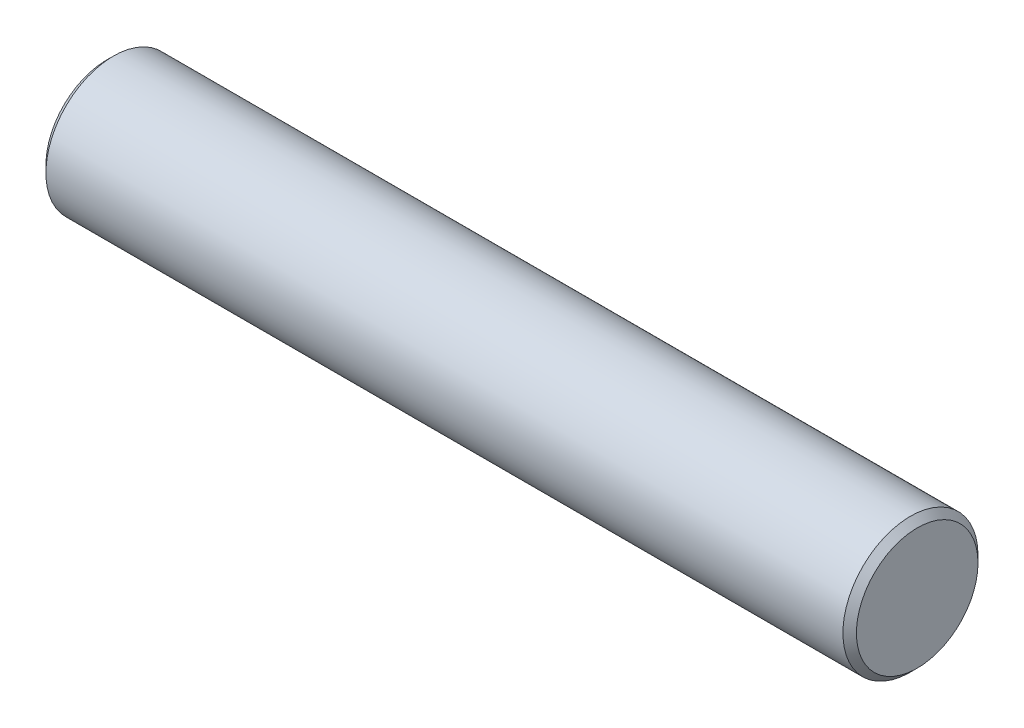
SolidWorks part; units mm, degrees
ref_plane "Front Plane" through (0, 0, 0) normal (0, 0, 1) x (1, 0, 0)
ref_plane "Top Plane" through (0, 0, 0) normal (0, 1, 0) x (1, 0, 0)
ref_plane "Right Plane" through (0, 0, 0) normal (1, 0, 0) x (0, 0, -1)
sketch "Sketch1" plane through (0, 0, 0) normal (1, 0, 0) x (0, 0, -1)
  circle A0 centre (0, 0) radius 1
  dimension "D1" = 2
extrude "Boss-Extrude1" add sketch "Sketch1" along normal blind 12
chamfer "Chamfer1" distance 0.1 angle 45 2 edges at (0, 0, -1) (12, 0, -1)
